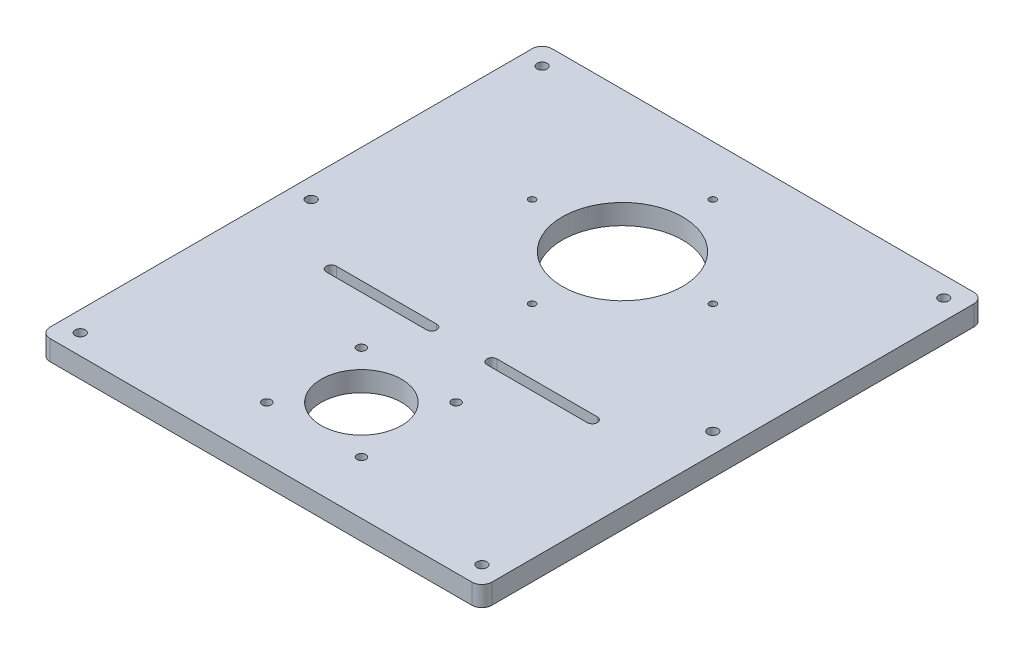
SolidWorks part; units mm, degrees
material "Acrylic (Medium-high impact)"
ref_plane "Front Plane" through (0, 0, 0) normal (0, 0, 1) x (1, 0, 0)
ref_plane "Top Plane" through (0, 0, 0) normal (0, 1, 0) x (1, 0, 0)
ref_plane "Right Plane" through (0, 0, 0) normal (1, 0, 0) x (0, 0, -1)
sketch "Sketch1" plane through (0, 0, 0) normal (0, 1, 0) x (1, 0, 0)
  line L0 (0, 0) -> (0, -50000) construction
  line L1 (-110, -80) -> (110, -80) construction
  line L2 (-23.57, -153.57) -> (23.57, -153.57) construction
  line L3 (-23.57, -153.57) -> (-23.57, -106.43) construction
  line L4 (-23.57, -106.43) -> (23.57, -106.43) construction
  line L5 (23.57, -153.57) -> (23.57, -106.43) construction
  line L6 (-23.57, -153.57) -> (23.57, -106.43) construction
  line L7 (-23.57, -106.43) -> (23.57, -153.57) construction
  line L8 (-110, 70) -> (110, 70)
  line L9 (-110, 70) -> (-110, -180)
  line L10 (-110, -180) -> (110, -180)
  line L11 (110, 70) -> (110, -180)
  line L12 (-65, -80) -> (-15, -80) construction
  line L13 (-65, -77.5) -> (-15, -77.5)
  line L14 (-65, -82.5) -> (-15, -82.5)
  line L15 (65, -80) -> (15, -80) construction
  line L16 (65, -77.5) -> (15, -77.5)
  line L17 (65, -82.5) -> (15, -82.5)
  circle A0 centre (0, 0) radius 30
  circle A1 centre (0, -130) radius 20
  circle A2 centre (-23.57, -106.43) radius 2.2
  circle A3 centre (23.57, -106.43) radius 2.2
  circle A4 centre (-23.57, -153.57) radius 2.2
  circle A5 centre (23.57, -153.57) radius 2.2
  arc A6 (-65, -77.5) -> (-65, -82.5) centre (-65, -80) ccw
  arc A7 (-15, -82.5) -> (-15, -77.5) centre (-15, -80) ccw
  arc A8 (65, -77.5) -> (65, -82.5) centre (65, -80) cw
  arc A9 (15, -82.5) -> (15, -77.5) centre (15, -80) cw
  point P19 (0, 70)
  point P22 (0, 30)
  point P25 (-40, -80)
  point P32 (40, -80)
  dimension "D1" = 60
  dimension "D2" = 4.4
  dimension "D3" = 40
  dimension "D4" = 47.14
  dimension "D5" = 130
  dimension "D6" = 70
  dimension "D7" = 220
  dimension "D8" = 180
  dimension "D9" = 80
  dimension "D10" = 5
  dimension "D11" = 50
  dimension "D12" = 15
extrude "Boss-Extrude1" add sketch "Sketch1" along normal blind 10
sketch "Sketch2" plane through (0, 10, 0) normal (0, 1, 0) x (1, 0, 0)
  line L17 (-100, -170) -> (100, -170)
  line L18 (100, -170) -> (100, 60)
  line L19 (-100, 60) -> (-100, -170)
  line L20 (100, 60) -> (-100, 60)
  line L21 (-100, -170) -> (100, -170) construction
  line L22 (100, -170) -> (100, 60) construction
  line L23 (-100, 60) -> (-100, -170) construction
  line L24 (100, 60) -> (-100, 60) construction
  circle A0 centre (-100, 60) radius 2.5
  circle A1 centre (100, 60) radius 2.5
  circle A2 centre (-100, -170) radius 2.5
  circle A3 centre (100, -170) radius 2.5
  circle A4 centre (-100, -55) radius 2.5
  circle A5 centre (100, -55) radius 2.5
  dimension "D2" = 5
  dimension "D1" = 10
extrude "Cut-Extrude1" cut sketch "Sketch2" against normal through all both and the other way through all
fillet "Fillet1" radius 5 4 edges at (110, 5, 180) (110, 5, -70) (-110, 5, 180) (-110, 5, -70)
sketch "Sketch4" plane through (0, 10, 0) normal (0, 1, 0) x (1, 0, 0)
  circle A0 centre (0, -45) radius 1.7
  dimension "D1" = 45
  dimension "D2" = 3.4
extrude "Cut-Extrude2" cut sketch "Sketch4" against normal through all both and the other way through all
pattern_circular "CirPattern1" count 4 over 360 about axis through (0, 0, 0) along (0, 1, 0) of "Cut-Extrude2"
